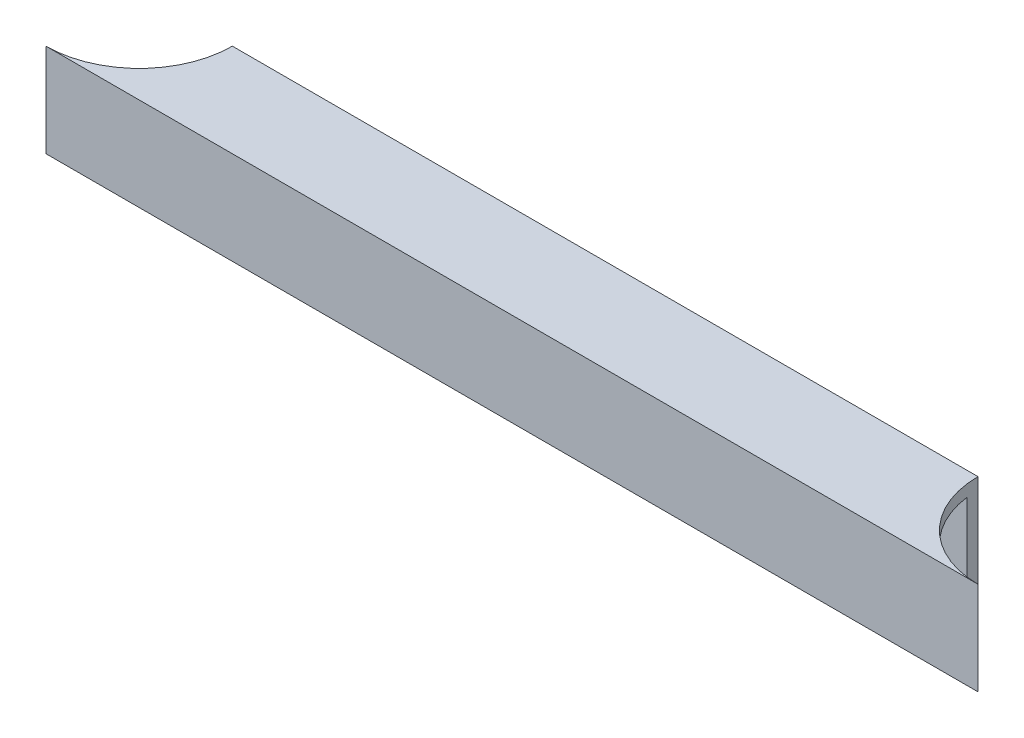
SolidWorks part; units mm, degrees
material "6061 Alloy"
ref_plane "Front Plane" through (0, 0, 0) normal (0, 0, 1) x (1, 0, 0)
ref_plane "Top Plane" through (0, 0, 0) normal (0, 1, 0) x (1, 0, 0)
ref_plane "Right Plane" through (0, 0, 0) normal (1, 0, 0) x (0, 0, -1)
sketch "Sketch1" plane through (0, 0, 0) normal (0, 1, 0) x (1, 0, 0)
  line L0 (-85.497, 49.3617) -> (-93.7459, 54.1242) construction
  line L1 (0, 146.647) -> (-127, -73.3235) construction
  line L2 (-127, -73.3235) -> (127, -73.3235) construction
  line L3 (127, -73.3235) -> (0, 146.647) construction
  line L4 (0, 197.447) -> (-170.9941, -98.7235) construction
  line L5 (-170.9941, -98.7235) -> (170.9941, -98.7235) construction
  line L6 (170.9941, -98.7235) -> (0, 197.447) construction
  line L7 (0, -98.7235) -> (0, -108.2485) construction
  line L8 (-127, -98.7235) -> (127, -98.7235)
  line L9 (0, 216.497) -> (-187.4919, -108.2485) construction
  line L10 (-187.4919, -108.2485) -> (187.4919, -108.2485) construction
  line L11 (187.4919, -108.2485) -> (0, 216.497) construction
  line L12 (101.6, -73.3235) -> (-101.6, -73.3235)
  circle A0 centre (0, 0) radius 73.3235 construction
  circle A1 centre (127, -73.3235) radius 25.4 construction
  circle A2 centre (-127, -73.3235) radius 25.4 construction
  circle A3 centre (0, 0) radius 98.7235 construction
  circle A4 centre (0, 0) radius 108.2485 construction
  arc A5 (-127, -98.7235) -> (-101.6, -73.3235) centre (-127, -73.3235) ccw
  arc A6 (127, -98.7235) -> (101.6, -73.3235) centre (127, -73.3235) cw
  dimension "D1" = 304.8
  dimension "D2" = 50.8
  dimension "D3" = 9.525
  dimension "D4" = 374.9837
  dimension "D5" = 25.4
extrude "Boss-Extrude1" add sketch "Sketch1" along normal blind 25.4 contours L8 A6 L12 A5
sketch "Sketch2" plane through (0, 0, 0) normal (1, 0, 0) x (0, 0, -1)
  line L0 (-95.5485, 22.225) -> (-76.4985, 22.225)
  line L1 (-98.7235, 25.4) -> (-73.3235, 25.4) construction
  line L2 (-98.7235, 25.4) -> (-98.7235, 0) construction
  line L3 (-98.7235, 0) -> (-73.3235, 0) construction
  line L4 (-73.3235, 25.4) -> (-73.3235, 0) construction
  line L5 (-76.4985, 22.225) -> (-76.4985, 3.175)
  line L6 (-95.5485, 3.175) -> (-76.4985, 3.175)
  line L7 (-95.5485, 22.225) -> (-95.5485, 3.175)
  dimension "D1" = 3.175
extrude "Cut-Extrude1" cut sketch "Sketch2" against normal through all both and the other way through all
